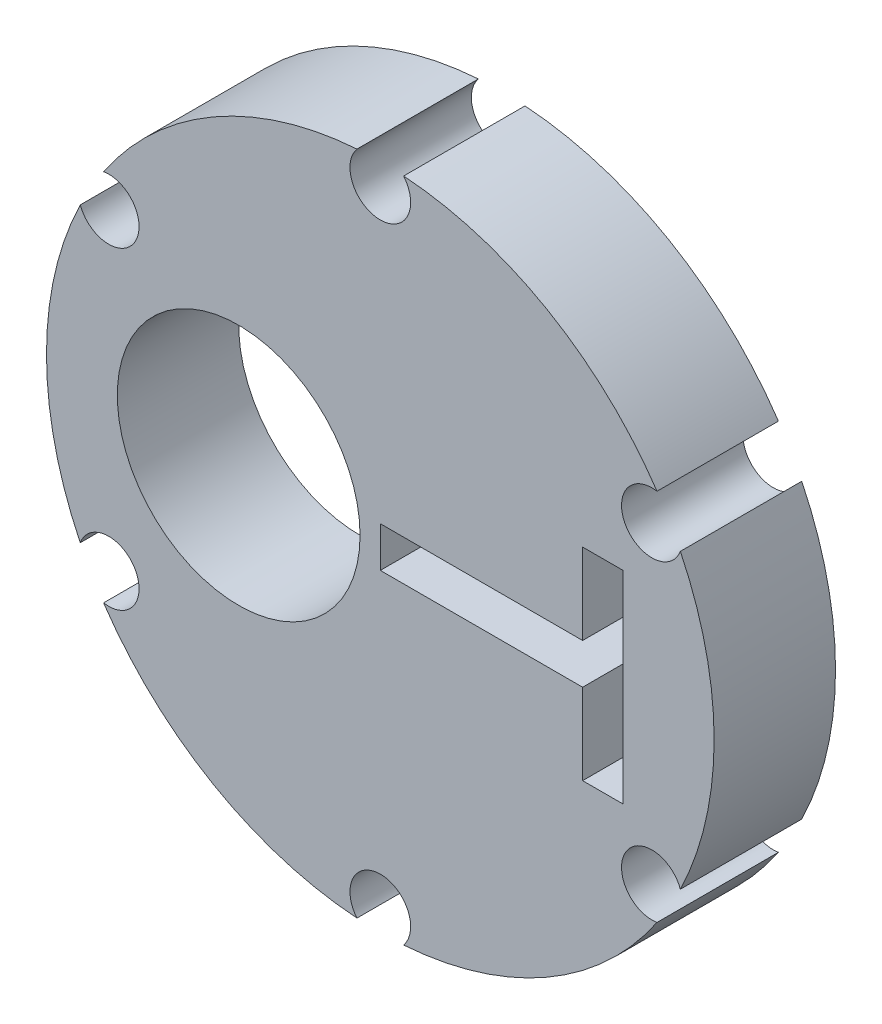
SolidWorks part; units mm, degrees
material "ABS"
ref_plane "Front Plane" through (0, 0, 0) normal (0, 0, 1) x (1, 0, 0)
ref_plane "Top Plane" through (0, 0, 0) normal (0, 1, 0) x (1, 0, 0)
ref_plane "Right Plane" through (0, 0, 0) normal (1, 0, 0) x (0, 0, -1)
sketch "Sketch1" plane through (0, 0, 0) normal (0, 0, 1) x (1, 0, 0)
  circle A0 centre (0, 0) radius 16.5
  dimension "D1" = 33
extrude "Boss-Extrude1" add sketch "Sketch1" along normal blind 6
sketch "Sketch2" plane through (0, 0, 6) normal (0, 0, 1) x (1, 0, 0)
  circle A0 centre (0, 15.5) radius 1.5
  circle A1 centre (13.4234, 7.75) radius 1.5
  circle A2 centre (13.4234, -7.75) radius 1.5
  circle A3 centre (0, -15.5) radius 1.5
  circle A4 centre (-13.4234, -7.75) radius 1.5
  circle A5 centre (-13.4234, 7.75) radius 1.5
  point P15 (0, 0)
  dimension "D1" = 3
  dimension "D2" = 15.5
  dimension "D3" = 6
extrude "Cut-Extrude1" cut sketch "Sketch2" against normal through all
sketch "Sketch3" plane through (0, 0, 6) normal (0, 0, 1) x (1, 0, 0)
  line L0 (-7, 0) -> (0, 0) construction
  circle A0 centre (-7, 0) radius 6
  dimension "D1" = 12
  dimension "D3" = 7
extrude "Cut-Extrude2" cut sketch "Sketch3" against normal through all
sketch "Sketch5" plane through (0, 0, 6) normal (0, 0, 1) x (1, 0, 0)
  line L1 (12, 5) -> (10, 5)
  line L2 (12, 5) -> (12, -5)
  line L3 (12, -5) -> (10, -5)
  line L4 (10, 5) -> (10, 1)
  line L5 (10, -1) -> (10, -5)
  line L6 (0, 1) -> (10, 1)
  line L7 (0, 1) -> (0, -1)
  line L8 (0, -1) -> (10, -1)
  point P10 (0, 0)
  dimension "D1" = 10
  dimension "D2" = 2
extrude "Cut-Extrude3" cut sketch "Sketch5" against normal through all
equation "\"smallPulleyTeeth\"= 30"
equation "\"largePulleyTeeth\"= 30"
equation "\"eighthThick\"= 3.0mm"
equation "\"sixteenthThick\" = 1.7mm"
equation "\"wheelEighthThick\"=3.0mm"
equation "\"quarterThick\"=6.0mm"
equation "\"OD\" = 145mm"
equation "\"puckAngle\" = 60.5deg"
equation "\"puckDiam\" = 76.5mm"
equation "\"axlePress\" = 5.9mm"
equation "\"D1@Boss-Extrude1\"=\"quarterThick\""
